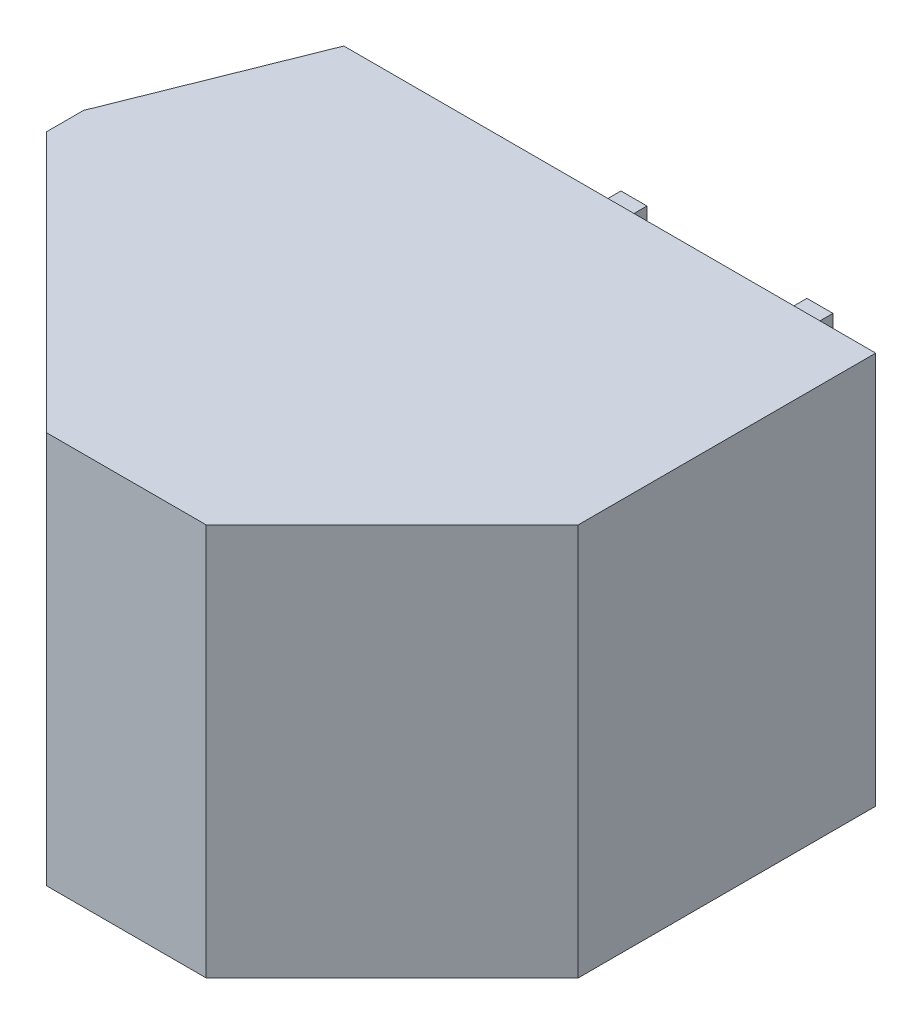
SolidWorks part; units mm, degrees
other "Детальный элемент1"
ref_plane "Спереди" through (0, 0, 0) normal (0, 0, 1) x (1, 0, 0)
ref_plane "Сверху" through (0, 0, 0) normal (0, 1, 0) x (1, 0, 0)
ref_plane "Справа" through (0, 0, 0) normal (1, 0, 0) x (0, 0, -1)
sketch "Эскиз1" plane through (0, 0, 0) normal (0, 0, 1) x (1, 0, 0)
  line L5 (0, 0) -> (16.3, 0)
  line L6 (0, 0) -> (0, 10.55)
  line L7 (0, 10.55) -> (16.3, 10.55)
  line L8 (16.3, 0) -> (16.3, 10.55)
  dimension "D1" = 16.3
  dimension "D2" = 10.55
extrude "Бобышка-Вытянуть1" add sketch "Эскиз1" along normal blind 13
chamfer "Фаска1" distance 5 angle 45 1 edges at (16.3, 5.275, 13)
chamfer "Фаска3" distance 2 distance2 5 1 edges at (0, 5.275, 0)
chamfer "Фаска4" distance 7 distance2 7 1 edges at (0, 5.275, 13)
sketch "Эскиз2" plane through (0, 0, 0) normal (0, 0, -1) x (-1, 0, 0)
  line L0 (-16.3, 10.55) -> (-2, 10.55) construction
  line L1 (-5.95, 1.7) -> (-6.65, 1.7)
  line L2 (-5.95, 1.7) -> (-5.95, 2.4)
  line L3 (-5.95, 2.4) -> (-6.65, 2.4)
  line L4 (-6.65, 1.7) -> (-6.65, 2.4)
  line L5 (-5.95, 1.7) -> (-6.65, 2.4) construction
  line L6 (-5.95, 2.4) -> (-6.65, 1.7) construction
  line L7 (-5.95, 6.7) -> (-6.65, 6.7)
  line L8 (-5.95, 6.7) -> (-5.95, 7.4)
  line L9 (-5.95, 7.4) -> (-6.65, 7.4)
  line L10 (-6.65, 6.7) -> (-6.65, 7.4)
  line L11 (-5.95, 6.7) -> (-6.65, 7.4) construction
  line L12 (-5.95, 7.4) -> (-6.65, 6.7) construction
  line L13 (-10.95, 1.7) -> (-11.65, 1.7)
  line L14 (-10.95, 1.7) -> (-10.95, 2.4)
  line L15 (-10.95, 2.4) -> (-11.65, 2.4)
  line L16 (-11.65, 1.7) -> (-11.65, 2.4)
  line L17 (-10.95, 1.7) -> (-11.65, 2.4) construction
  line L18 (-10.95, 2.4) -> (-11.65, 1.7) construction
  line L19 (-11.65, 7.4) -> (-10.95, 7.4)
  line L20 (-11.65, 7.4) -> (-11.65, 6.7)
  line L21 (-11.65, 6.7) -> (-10.95, 6.7)
  line L22 (-10.95, 7.4) -> (-10.95, 6.7)
  line L23 (-11.65, 7.4) -> (-10.95, 6.7) construction
  line L24 (-11.65, 6.7) -> (-10.95, 7.4) construction
  line L25 (-16.3, 0) -> (-16.3, 10.55) construction
  point P0 (-6.3, 2.05)
  point P5 (-6.3, 7.05)
  point P10 (-11.3, 2.05)
  point P15 (-11.3, 7.05)
  point P20 (0, 0)
  point P21 (0, 0)
  point P22 (0, 0)
  point P23 (0, 0)
  point P24 (0, 0)
  point P25 (0, 0)
  dimension "D1" = 5
  dimension "D2" = 5
  dimension "D3" = 3.5
  dimension "D4" = 5
  dimension "D5" = 0.7
  dimension "D6" = 0.7
extrude "Бобышка-Вытянуть2" add sketch "Эскиз2" along normal blind 3.5
